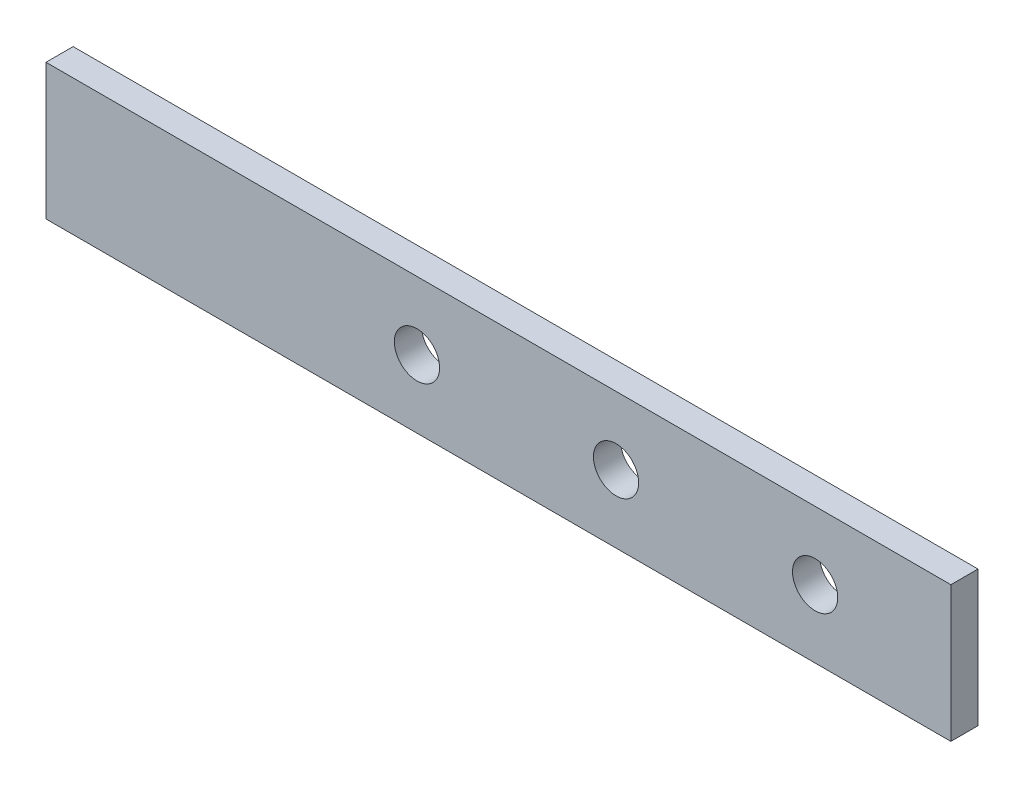
SolidWorks part; units mm, degrees
ref_plane "Front Plane" through (0, 0, 0) normal (0, 0, 1) x (1, 0, 0)
ref_plane "Top Plane" through (0, 0, 0) normal (0, 1, 0) x (1, 0, 0)
ref_plane "Right Plane" through (0, 0, 0) normal (1, 0, 0) x (0, 0, -1)
sketch "Sketch2" plane through (0, 0, 0) normal (0, 0, 1) x (1, 0, 0)
  line L1 (-500, 75) -> (500, 75)
  line L2 (-500, 75) -> (-500, -75)
  line L3 (-500, -75) -> (500, -75)
  line L4 (500, 75) -> (500, -75)
  line L5 (-500, 75) -> (500, -75) construction
  line L6 (-500, -75) -> (500, 75) construction
  circle A1 centre (130, 0) radius 25
  circle A2 centre (-90, 0) radius 25
  circle A3 centre (350, 0) radius 25
  point P0 (0, 0)
  point P12 (0, 0)
  point P13 (0, 0)
  dimension "D6" = 50
  dimension "D3" = 50
  dimension "D1" = 1000
  dimension "D2" = 150
  dimension "D4" = 75
  dimension "D5" = 220
  dimension "D7" = 75
  dimension "D8" = 75
  dimension "D9" = 150
  dimension "D10" = 220
extrude "Boss-Extrude1" add sketch "Sketch2" against normal blind 30
